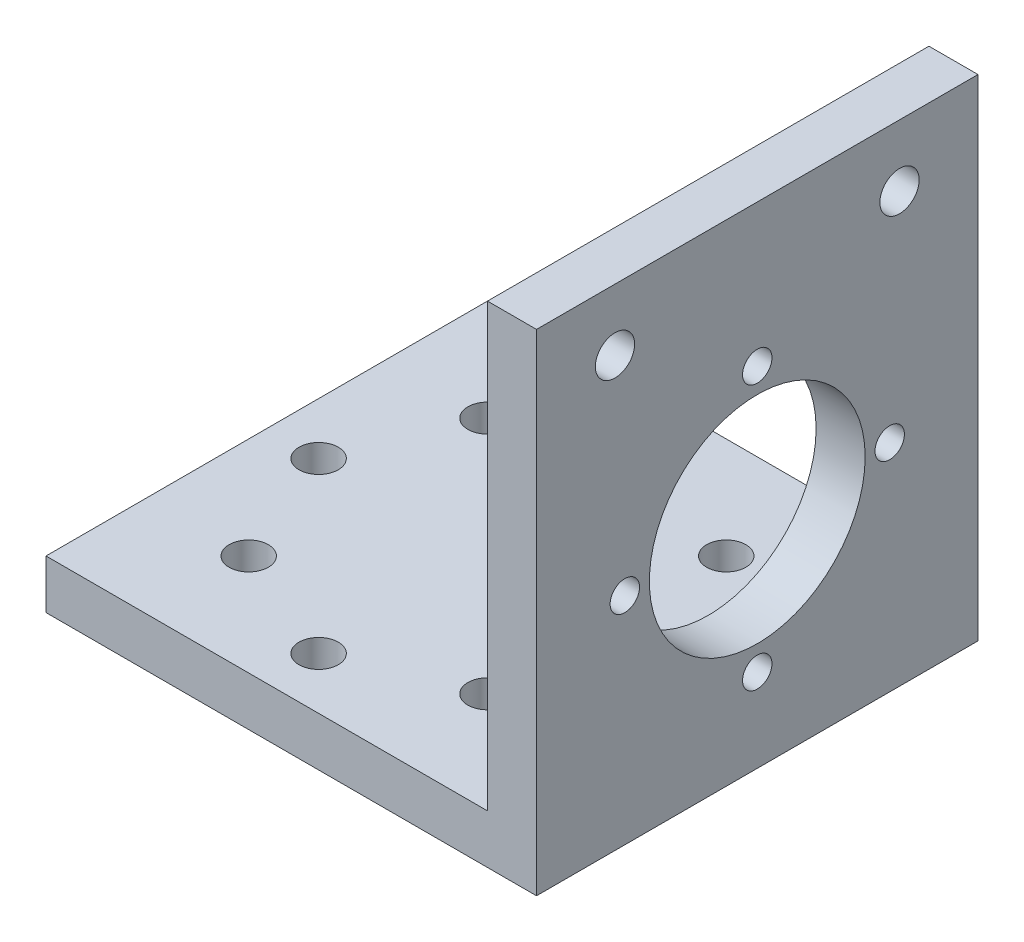
SolidWorks part; units mm, degrees
ref_plane "Front Plane" through (0, 0, 0) normal (0, 0, 1) x (1, 0, 0)
ref_plane "Top Plane" through (0, 0, 0) normal (0, 1, 0) x (1, 0, 0)
ref_plane "Right Plane" through (0, 0, 0) normal (1, 0, 0) x (0, 0, -1)
sketch "Sketch1" plane through (0, 0, 0) normal (0, 0, 1) x (1, 0, 0)
  line L0 (0, 50) -> (0, 0)
  line L1 (0, 0) -> (-50, 0)
  line L2 (-50, 0) -> (-50, 5)
  line L3 (-50, 5) -> (-5, 5)
  line L4 (-5, 5) -> (-5, 50)
  line L5 (-5, 50) -> (0, 50)
  dimension "D1" = 50
  dimension "D2" = 5
  dimension "D3" = 50
  dimension "D4" = 5
extrude "Boss-Extrude1" add sketch "Sketch1" along normal blind 45
sketch "Sketch2" plane through (0, 0, 0) normal (1, 0, 0) x (0, 0, -1)
  line L0 (-22.5, 50) -> (-22.5, 0) construction
  line L1 (-45, 50) -> (0, 50) construction
  line L2 (-45, 0) -> (0, 0) construction
  circle A0 centre (-22.5, 22) radius 11
  dimension "D1" = 22
  dimension "D2" = 28
extrude "Cut-Extrude1" cut sketch "Sketch2" against normal blind 5
sketch "Sketch3" plane through (0, 0, 0) normal (1, 0, 0) x (0, 0, -1)
  line L0 (-22.5, 50) -> (-22.5, 0) construction
  line L1 (-45, 50) -> (0, 50) construction
  line L2 (-45, 0) -> (0, 0) construction
  circle A0 centre (-22.5, 35.5) radius 1.5
  circle A1 centre (-22.5, 22) radius 11 construction
  circle A2 centre (-9, 22) radius 1.5
  circle A3 centre (-22.5, 8.5) radius 1.5
  circle A4 centre (-36, 22) radius 1.5
  point P10 (-22.5, 19)
  point P19 (-22.5, 22)
  dimension "D1" = 3
  dimension "D2" = 13.5
  dimension "D3" = 4
extrude "Cut-Extrude2" cut sketch "Sketch3" against normal blind 5
sketch "Sketch4" plane through (0, 5, 0) normal (0, 1, 0) x (1, 0, 0)
  line L0 (-27.5, 0) -> (-27.5, -45) construction
  line L1 (-5, 0) -> (-50, 0) construction
  line L2 (-5, -45) -> (-50, -45) construction
  line L3 (-50, -22.5) -> (-5, -22.5) construction
  line L4 (-50, -45) -> (-50, 0) construction
  line L5 (-5, -45) -> (-5, 0) construction
  circle A0 centre (-27.5, -5.2903) radius 2
  circle A1 centre (-15.3309, -10.3309) radius 2
  circle A2 centre (-10.2903, -22.5) radius 2
  circle A3 centre (-15.3309, -34.6691) radius 2
  circle A4 centre (-27.5, -39.7097) radius 2
  circle A5 centre (-39.6691, -34.6691) radius 2
  circle A6 centre (-44.7097, -22.5) radius 2
  circle A7 centre (-39.6691, -10.3309) radius 2
  point P14 (-27.5, -22.5)
  point P31 (-27.5, -22.5)
  dimension "D1" = 4
  dimension "D2" = 8
extrude "Cut-Extrude3" cut sketch "Sketch4" against normal blind 5
sketch "Sketch5" plane through (0, 0, 0) normal (1, 0, 0) x (0, 0, -1)
  line L0 (-22.5, 50) -> (-22.5, 0) construction
  line L1 (-45, 50) -> (0, 50) construction
  line L2 (-45, 0) -> (0, 0) construction
  line L3 (-45, 0) -> (-45, 50) construction
  circle A0 centre (-37, 43.7084) radius 2
  circle A1 centre (-8, 43.7084) radius 2
  dimension "D1" = 4
  dimension "D2" = 8
extrude "Cut-Extrude4" cut sketch "Sketch5" against normal blind 5
